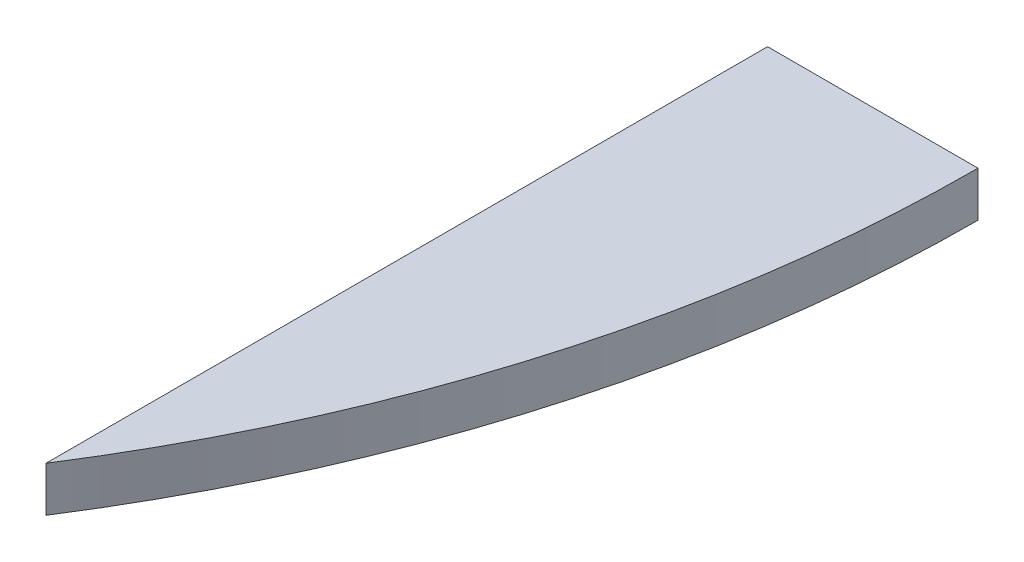
SolidWorks part; units mm, degrees
ref_plane "Front Plane" through (0, 0, 0) normal (0, 0, 1) x (1, 0, 0)
ref_plane "Top Plane" through (0, 0, 0) normal (0, 1, 0) x (1, 0, 0)
ref_plane "Right Plane" through (0, 0, 0) normal (1, 0, 0) x (0, 0, -1)
sketch "Sketch1" plane through (0, 0, 0) normal (0, 1, 0) x (1, 0, 0)
  line L0 (0, 0) -> (0, 48)
  line L1 (0, 48) -> (14, 48)
  arc A0 (14, 48) -> (0, 0) centre (-75.2857, 48) cw
  dimension "D3" = 89.2857
  dimension "D1" = 14
  dimension "D2" = 48
extrude "Boss-Extrude1" add sketch "Sketch1" along normal blind 3
